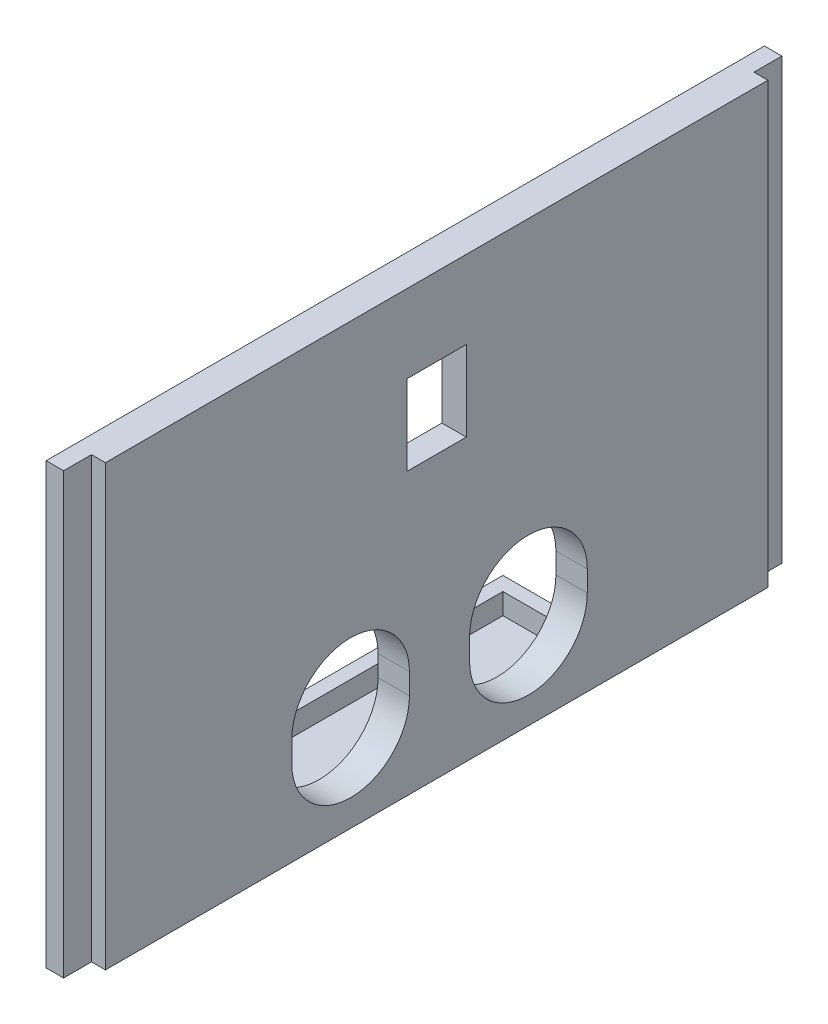
SolidWorks part; units mm, degrees
ref_plane "정면" through (0, 0, 0) normal (0, 0, 1) x (1, 0, 0)
ref_plane "윗면" through (0, 0, 0) normal (0, 1, 0) x (1, 0, 0)
ref_plane "우측면" through (0, 0, 0) normal (1, 0, 0) x (0, 0, -1)
sketch "스케치1" plane through (0, 0, 0) normal (0, 1, 0) x (1, 0, 0)
  line L0 (-2.25, 51.5) -> (0.25, 51.5)
  line L1 (-2.25, 51.5) -> (-2.25, -51.5)
  line L2 (-2.25, -51.5) -> (0.25, -51.5)
  line L3 (0.25, 51.5) -> (0.25, -51.5)
  line L4 (0.25, 47.5) -> (2.25, 47.5)
  line L5 (0.25, 47.5) -> (0.25, -47.5)
  line L6 (0.25, -47.5) -> (2.25, -47.5)
  line L7 (2.25, 47.5) -> (2.25, -47.5)
  dimension "D1" = 2.5
  dimension "D2" = 4
extrude "보스-돌출1" add sketch "스케치1" along normal blind 63 contours L3 L0 L1 L2 | L7 L4 L3 L6
sketch "스케치2" plane through (-2.25, 0, 0) normal (-1, 0, 0) x (0, 0, 1)
  line L0 (-51.5, 0) -> (51.5, 0) construction
  line L1 (-22.5, 22.5) -> (22.5, 22.5)
  line L2 (-22.5, 22.5) -> (-22.5, 2)
  line L3 (-22.5, 2) -> (22.5, 2)
  line L4 (22.5, 22.5) -> (22.5, 2)
  line L5 (51.5, 63) -> (51.5, 0) construction
  dimension "D1" = 45
  dimension "D2" = 20.5
  dimension "D3" = 2
  dimension "D4" = 29
sketch "스케치5" plane through (-2.25, 0, 0) normal (-1, 0, 0) x (0, 0, 1)
  line L1 (-25, 2) -> (25, 2)
  line L2 (-25, 2) -> (-25, 0)
  line L3 (-25, 0) -> (25, 0)
  line L4 (25, 2) -> (25, 0)
  line L5 (-51.5, 63) -> (-51.5, 0) construction
  dimension "D1" = 26.5
  dimension "D2" = 50
extrude "보스-돌출2" add sketch "스케치5" along normal blind 11
sketch "스케치7" plane through (0, 2, 0) normal (0, 1, 0) x (1, 0, 0)
  line L0 (-2.25, 23) -> (-11.25, 23)
  line L1 (-11.25, 23) -> (-11.25, -23)
  line L2 (-11.25, -23) -> (-2.25, -23)
  line L3 (-2.25, 23) -> (-2.25, 25)
  line L4 (-2.25, -25) -> (-2.25, 25)
  line L5 (-2.25, 25) -> (-13.25, 25)
  line L6 (-13.25, 25) -> (-13.25, -25)
  line L7 (-13.25, -25) -> (-2.25, -25)
  line L8 (-2.25, -25) -> (-2.25, -23)
  line L9 (-2.25, 25) -> (-13.25, 25)
  line L10 (-13.25, 25) -> (-13.25, -25)
  line L11 (-13.25, -25) -> (-2.25, -25)
  dimension "D1" = 0
  dimension "D2" = 2
extrude "보스-돌출3" add sketch "스케치7" along normal blind 3
sketch "스케치9" plane through (0, 2, 0) normal (0, 1, 0) x (1, 0, 0)
  line L0 (-11.25, -23) -> (-11.25, 23) construction
  line L1 (-10.75, 22.5) -> (-9, 22.5)
  line L2 (-10.75, 22.5) -> (-10.75, -22.5)
  line L3 (-10.75, -22.5) -> (-9, -22.5)
  line L4 (-9, 22.5) -> (-9, -22.5)
  line L5 (-2.25, -23) -> (-11.25, -23) construction
  dimension "D1" = 45
  dimension "D2" = 1.75
  dimension "D3" = 0.5
  dimension "D4" = 0.5
sketch "스케치10" plane through (2.25, 0, 0) normal (1, 0, 0) x (0, 0, -1)
  line L0 (-12.34, 12.25) -> (-12.34, 15.25) construction
  line L1 (13.16, 12.25) -> (13.16, 15.25) construction
  line L2 (-20.78, 15.25) -> (-20.78, 12.25)
  line L3 (-3.9, 15.25) -> (-3.9, 12.25)
  line L4 (4.72, 15.25) -> (4.72, 12.25)
  line L5 (21.6, 15.25) -> (21.6, 12.25)
  arc A0 (-20.78, 12.25) -> (-3.9, 12.25) centre (-12.34, 12.25) ccw
  arc A1 (4.72, 12.25) -> (21.6, 12.25) centre (13.16, 12.25) ccw
  arc A2 (-3.9, 15.25) -> (-20.78, 15.25) centre (-12.34, 15.25) ccw
  arc A3 (21.6, 15.25) -> (4.72, 15.25) centre (13.16, 15.25) ccw
  dimension "D1" = 16.88
  dimension "D2" = 16.88
  dimension "D4" = 16.88
  dimension "D5" = 16.88
  dimension "D3" = 3
extrude "컷-돌출1" cut sketch "스케치10" against normal up to surface (4.5 mm away) up to face at (-2.25, 12.5, 0)
sketch "스케치11" plane through (-2.25, 0, 0) normal (-1, 0, 0) x (0, 0, 1)
  line L0 (-51.5, 63) -> (-51.5, 0) construction
  line L1 (-12.5, 57) -> (12.5, 57)
  line L2 (-12.5, 57) -> (-12.5, 30)
  line L3 (-12.5, 30) -> (12.5, 30)
  line L4 (12.5, 57) -> (12.5, 30)
  line L7 (-4.25, 51.8) -> (4.25, 51.8)
  line L8 (-4.25, 51.8) -> (-4.25, 40.3)
  line L9 (-4.25, 40.3) -> (4.25, 40.3)
  line L10 (4.25, 51.8) -> (4.25, 40.3)
  dimension "D1" = 25
  dimension "D2" = 27
  dimension "D3" = 39
  dimension "D5" = 8.25
  dimension "D7" = 11.5
  dimension "D8" = 8.5
extrude "컷-돌출2" cut sketch "스케치11" against normal up to surface (4.5 mm away) contours L10 L7 L8 L9 up to face at (2.25, 13.75, 12.34)
sketch "스케치12" plane through (-2.25, 0, 0) normal (-1, 0, 0) x (0, 0, 1)
  line L0 (-13, 57.5) -> (-13, 29.5)
  line L1 (-12.5, 57) -> (12.5, 57)
  line L2 (-12.5, 57) -> (-12.5, 30)
  line L3 (-12.5, 30) -> (12.5, 30)
  line L4 (12.5, 57) -> (12.5, 30)
  line L5 (-13, 29.5) -> (13, 29.5)
  line L6 (13, 57.5) -> (13, 29.5)
  line L7 (-13, 57.5) -> (13, 57.5)
  line M21 (4.25, 51.8) -> (4.25, 40.3)
  line M22 (4.25, 40.3) -> (-4.25, 40.3)
  line M23 (-4.25, 40.3) -> (-4.25, 51.8)
  line M24 (-4.25, 51.8) -> (4.25, 51.8)
  dimension "D1" = 0.5
extrude "컷-돌출3" cut sketch "스케치12" against normal blind 1 contours L4 L1 L2 L3 M24 M21 M22 M23 | L7 L0 L5 L6 L1 L4 L3 L2
sketch "스케치13" plane through (-2.25, 0, 0) normal (-1, 0, 0) x (0, 0, 1)
  line L0 (-51.5, 63) -> (-51.5, 0) construction
  line L1 (-15, 29.5) -> (15, 29.5)
  line L2 (-15, 29.5) -> (-15, 27.5)
  line L3 (-15, 27.5) -> (15, 27.5)
  line L4 (15, 29.5) -> (15, 27.5)
  line L6 (-13, 29.5) -> (13, 29.5) construction
  dimension "D1" = 36.5
  dimension "D2" = 30
  dimension "D3" = 2
extrude "보스-돌출4" add sketch "스케치13" along normal blind 4
sketch "스케치14" plane through (0, 29.5, 0) normal (0, 1, 0) x (1, 0, 0)
  line L0 (-2.25, -13) -> (-2.25, -15)
  line L1 (-6.25, 15) -> (-2.25, 15)
  line L2 (-6.25, 15) -> (-6.25, -15)
  line L3 (-6.25, -15) -> (-2.25, -15)
  line L4 (-2.25, 15) -> (-2.25, 13)
  line L5 (-4.25, 13) -> (-2.25, 13)
  line L6 (-4.25, 13) -> (-4.25, -13)
  line L7 (-4.25, -13) -> (-2.25, -13)
  dimension "D1" = 2
  dimension "D2" = 2
  dimension "D3" = 2
  dimension "D4" = 2
extrude "보스-돌출5" add sketch "스케치14" along normal blind 3
